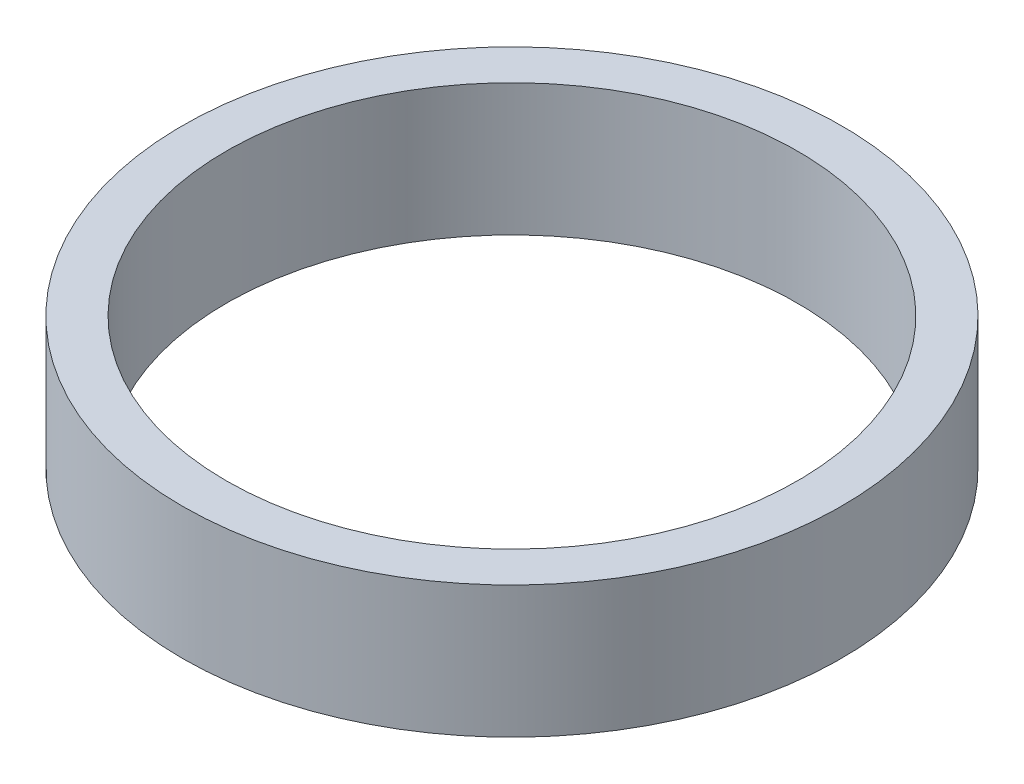
SolidWorks part; units mm, degrees
ref_plane "Front Plane" through (0, 0, 0) normal (0, 0, 1) x (1, 0, 0)
ref_plane "Top Plane" through (0, 0, 0) normal (0, 1, 0) x (1, 0, 0)
ref_plane "Right Plane" through (0, 0, 0) normal (1, 0, 0) x (0, 0, -1)
sketch "Sketch1" plane through (0, 0, 0) normal (0, 1, 0) x (1, 0, 0)
  circle A0 centre (0, 0) radius 6.5
  circle A1 centre (0, 0) radius 7.5
extrude "Boss-Extrude1" add sketch "Sketch1" along normal blind 3
